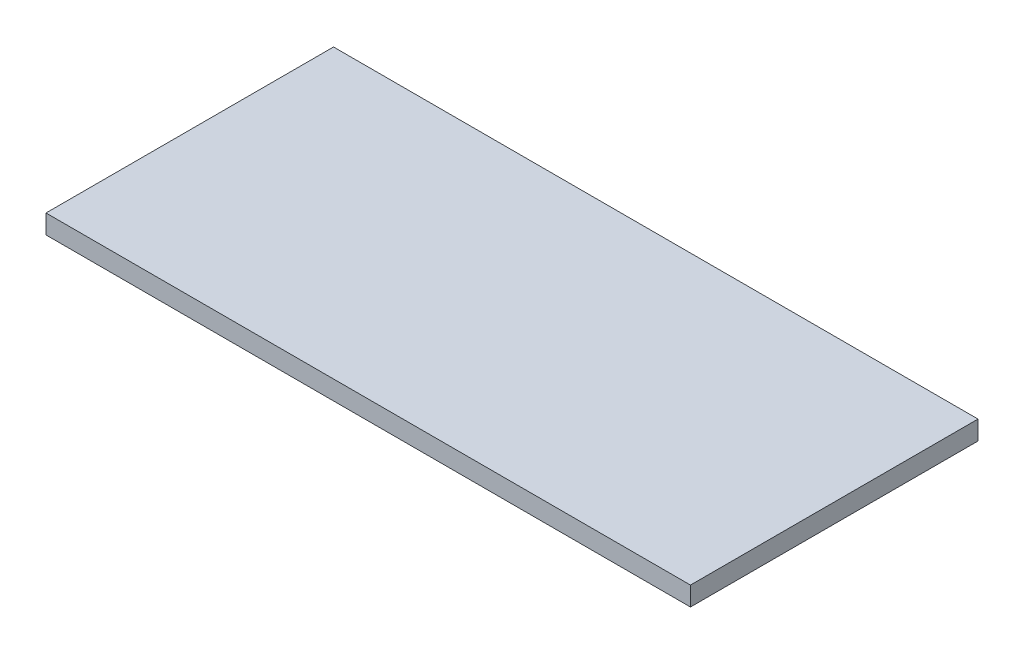
SolidWorks part; units mm, degrees
ref_plane "Front Plane" through (0, 0, 0) normal (0, 0, 1) x (1, 0, 0)
ref_plane "Top Plane" through (0, 0, 0) normal (0, 1, 0) x (1, 0, 0)
ref_plane "Right Plane" through (0, 0, 0) normal (1, 0, 0) x (0, 0, -1)
sketch "Sketch1" plane through (0, 0, 0) normal (0, 1, 0) x (1, 0, 0)
  line L1 (-25.7969, -11.5094) -> (25.7969, -11.5094)
  line L2 (-25.7969, -11.5094) -> (-25.7969, 11.5094)
  line L3 (-25.7969, 11.5094) -> (25.7969, 11.5094)
  line L4 (25.7969, -11.5094) -> (25.7969, 11.5094)
  line L5 (-25.7969, -11.5094) -> (25.7969, 11.5094) construction
  line L6 (-25.7969, 11.5094) -> (25.7969, -11.5094) construction
  point P0 (0, 0)
  dimension "D1" = 51.5938
  dimension "D2" = 23.0188
extrude "Boss-Extrude1" add sketch "Sketch1" along normal blind 1.524
